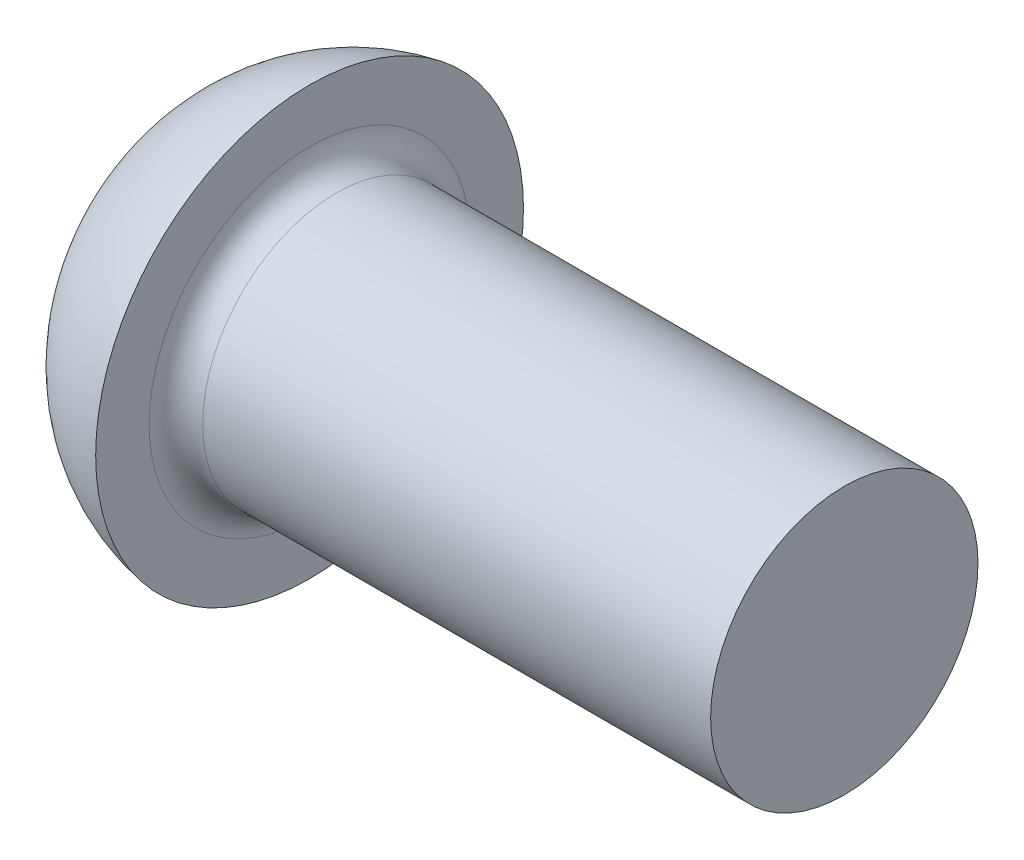
SolidWorks part; units mm, degrees
ref_plane "Front" through (0, 0, 0) normal (0, 0, 1) x (1, 0, 0)
ref_plane "Top" through (0, 0, 0) normal (0, 1, 0) x (1, 0, 0)
ref_plane "Right" through (0, 0, 0) normal (1, 0, 0) x (0, 0, -1)
sketch "Sketch1" plane through (0, 0, 0) normal (0, 1, 0) x (1, 0, 0)
  line L0 (-13.6293, 0) -> (11.3577, 0) construction
  line L1 (1.2, 1) -> (5.2, 1)
  line L2 (5.2, 1) -> (5.2, 0)
  line L3 (1.2, 1) -> (1.2, 1.6)
  line L4 (5.2, 0) -> (0, 0)
  arc A0 (1.2, 1.6) -> (0.0688, 0.5584) centre (1.4269, 0.2185) ccw
  arc A1 (0, 0) -> (0.0688, 0.5584) centre (2.3, 0) cw
  dimension "r2" = 1.4
  dimension "r1" = 2.3
  dimension "d" = 2
  dimension "dk" = 3.2
  dimension "l" = 4
  dimension "k" = 1.2
revolve "Revolve1" add sketch "Sketch1" angle 360 about L0
cosmetic thread "ThreadCosmetic1" [suppressed] parameters "l0"=4, "dm"=1.86
fillet "Fillet2" radius 0.2 1 edges at (1.2, 0, 1)
sketch "Sketch4" plane through (0, 0, 0) normal (0, 1, 0) x (1, 0, 0)
  line L0 (4.7828, 0) -> (7.1391, 0) construction
  line L1 (5.2, -1) -> (5.2, 1) construction
  line L2 (5.9335, 0) -> (5.9335, 21)
  line L3 (5.9335, 21) -> (5.1963, 21)
  line L4 (5.1963, 21) -> (5.2, 0)
  line L5 (5.2, 0) -> (5.9335, 0)
  dimension "D1" = 89.99
  dimension "D2" = 0.7335
  dimension "D3" = 21
revolve "Cut-Revolve1" cut sketch "Sketch4" angle 360 about L0
sketch "Sketch2" plane through (0, 0, 0) normal (1, 0, 0) x (0, 0, -1)
  line L0 (-2.278, 0) -> (2.6944, 0) construction
  line L1 (0, -2.1234) -> (0, 2.1948) construction
  line L2 (-0.3125, 0.3125) -> (-1.25, 0.3125)
  line L3 (0.3125, -1.25) -> (-0.3125, -1.25)
  line L4 (0.3125, -1.25) -> (0.3125, -0.3125)
  line L5 (0.3125, 1.25) -> (-0.3125, 1.25)
  line L6 (-0.3125, -1.25) -> (-0.3125, -0.3125)
  line L7 (1.25, 0.3125) -> (0.3125, 0.3125)
  line L8 (1.25, 0.3125) -> (1.25, -0.3125)
  line L9 (1.25, -0.3125) -> (0.3125, -0.3125)
  line L10 (-1.25, 0.3125) -> (-1.25, -0.3125)
  line L11 (-0.3125, 0.3125) -> (-0.3125, 1.25)
  line L12 (-0.3125, -0.3125) -> (-1.25, -0.3125)
  line L13 (0.3125, 0.3125) -> (0.3125, 1.25)
  point P19 (-0.3125, 0.3125)
  point P22 (0.3125, 0.3125)
  point P27 (-0.3125, -0.3125)
  dimension "m" = 2.5
  dimension "D2" = 2.5
  dimension "D3" = 0.625
  dimension "D4" = 0.625
ref_plane "Plane1" through (1.45, 0, 0) normal (1, 0, 0) x (0, 0, -1)
sketch "Sketch5" plane through (1.45, 0, 0) normal (1, 0, 0) x (0, 0, -1)
  point P0 (0, 0)
loft "Cut-Loft1" cut profiles "Sketch5", "Sketch2"
sketch "Sketch6" [suppressed] plane through (0, 0, 0) normal (0, 0, 1) x (1, 0, 0)
  line L0 (1.6, 1.2) -> (1.67, 1.2)
  line L1 (1.67, 1.2) -> (1.67, 1)
  line L2 (1.67, 1) -> (1.635, 0.9394)
  line L3 (1.6, 1) -> (1.635, 0.9394)
  line L4 (1.6, 1.2) -> (1.6, 1)
  line L5 (10.7743, 0) -> (0, 0) construction
  line L6 (1.6, 1) -> (1.67, 1) construction
  line L7 (1.635, 1) -> (1.635, 0.9394) construction
  line L8 (4.6, 1) -> (1.8, 1) construction
  point P5 (1.635, 1.2)
  dimension "D1" = 0.2
  dimension "D2" = 0.07
  dimension "D3" = 5
revolve "Cut-Revolve10" [suppressed] cut sketch "Sketch6" angle 360 about L5
pattern_linear "LPattern10" [suppressed] count 36 spacing 0.14 along (1, 0, 0)
equation "\"D4@Sketch2\" = \"D3@Sketch2\""
equation "\"D2@Sketch2\" = \"m@Sketch2\""
equation "\"D3@Sketch2\" = \"m@Sketch2\" / 4"
equation "\"D2@Sketch6\" = (  \"d@Sketch1\" - \"dm@ThreadCosmetic1\" )  / 2"
equation "\"D3@Sketch6\" = \"l0@ThreadCosmetic1\" + \"d@Sketch1\" / 2"
equation "\"D3@LPattern10\" = \"D2@Sketch6\" *2"
equation "\"D1@LPattern10\" = \"D3@Sketch6\" / \"D3@LPattern10\""
